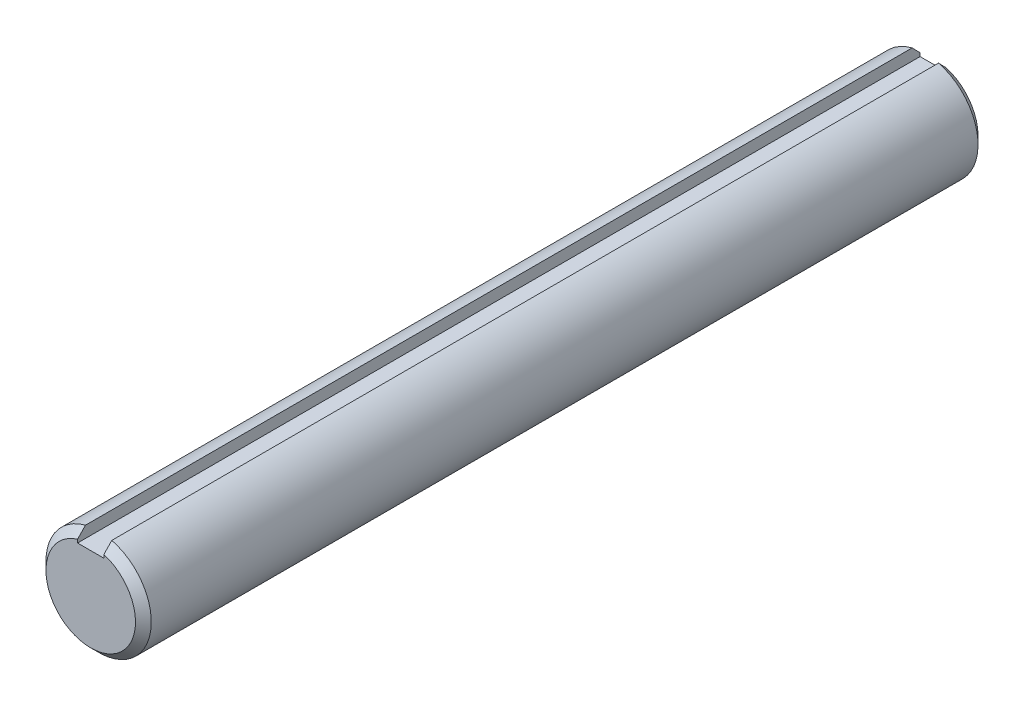
SolidWorks part; units mm, degrees
ref_plane "Front" through (0, 0, 0) normal (0, 0, 1) x (1, 0, 0)
ref_plane "Top" through (0, 0, 0) normal (0, 1, 0) x (1, 0, 0)
ref_plane "Right" through (0, 0, 0) normal (1, 0, 0) x (0, 0, -1)
sketch "Sketch1" plane through (0, 0, 0) normal (0, 0, 1) x (1, 0, 0)
  circle A0 centre (0, 0) radius 4.7625
  dimension "dia" = 9.525
extrude "Extrude1" add sketch "Sketch1" along normal mid plane 76.2
sketch "Sketch2" plane through (0, 0, 0) normal (1, 0, 0) x (0, 0, -1)
  point P0 (-38.1, 4.7625)
  point P1 (38.1, 4.7625)
  point P2 (38.1, -4.7625)
chamfer "Chamfer1" distance 0.7144 angle 45 2 edges at (4.7625, 0, -38.1) (4.7625, 0, 38.1)
sketch "Sketch3" plane through (0, 0, 0) normal (0, 0, 1) x (1, 0, 0)
  line L1 (-1.1906, 4.7625) -> (1.1906, 4.7625)
  line L2 (-1.1906, 4.7625) -> (-1.1906, 3.5719)
  line L3 (-1.1906, 3.5719) -> (1.1906, 3.5719)
  line L4 (1.1906, 4.7625) -> (1.1906, 3.5719)
  dimension "key wd" = 2.3813
  dimension "key dp" = 1.1906
extrude "Extrude2" cut sketch "Sketch3" against normal through all and the other way through all
equation "\"D1@Chamfer1\" = \"dia@Sketch1\" * .075"
